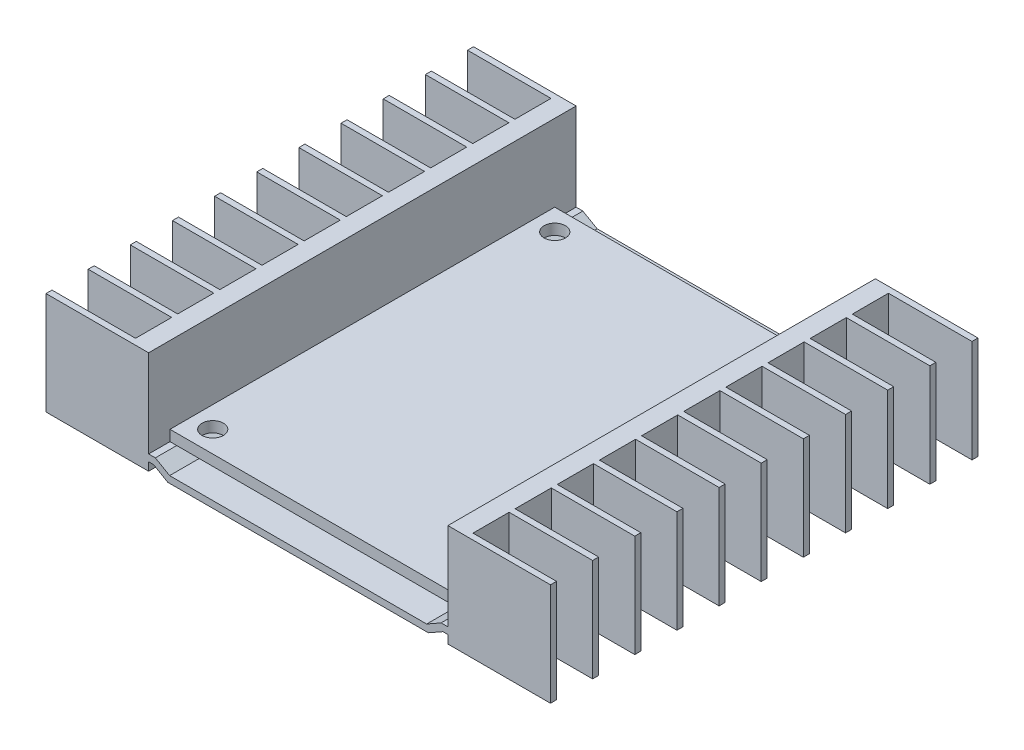
SolidWorks part; units mm, degrees
ref_plane "Front Plane" through (0, 0, 0) normal (0, 0, 1) x (1, 0, 0)
ref_plane "Top Plane" through (0, 0, 0) normal (0, 1, 0) x (1, 0, 0)
ref_plane "Right Plane" through (0, 0, 0) normal (1, 0, 0) x (0, 0, -1)
sketch "Sketch1" plane through (0, 0, 0) normal (0, 1, 0) x (1, 0, 0)
  line L1 (-99.1601, -6.7891) -> (-24.2301, -6.7891) construction
  line L2 (-99.1601, -6.7891) -> (-99.1601, -70.2891) construction
  line L3 (-99.1601, -70.2891) -> (-24.2301, -70.2891) construction
  line L4 (-24.2301, -6.7891) -> (-24.2301, -70.2891) construction
  line L5 (-83.9201, -9.9641) -> (-39.4701, -9.9641)
  line L6 (-83.9201, -9.9641) -> (-83.9201, -67.1141)
  line L7 (-83.9201, -67.1141) -> (-39.4701, -67.1141)
  line L8 (-39.4701, -9.9641) -> (-39.4701, -67.1141)
  circle A0 centre (-80.7451, -63.9391) radius 1.5875
  circle A1 centre (-42.6451, -63.9391) radius 1.5875
  circle A2 centre (-42.6451, -13.1391) radius 1.5875
  circle A3 centre (-80.7451, -13.1391) radius 1.5875
  dimension "D3" = 3.175
  dimension "D4" = 2
  dimension "D1" = 63.5
  dimension "D2" = 74.93
  dimension "D6" = 50.8
  dimension "D7" = 38.1
  dimension "D8" = 6.35
  dimension "D9" = 18.415
  dimension "D10" = 3.175
  dimension "D11" = 3.175
  dimension "D12" = 3.175
  dimension "D13" = 3.175
  dimension "D14" = 57.15
  dimension "D5" = 2
extrude "Boss-Extrude1" add sketch "Sketch1" along normal blind 1.5875
sketch "Sketch2" plane through (0, 1.5875, 0) normal (0, 1, 0) x (1, 0, 0)
  line L0 (-99.1601, -6.7891) -> (-83.9201, -6.7891)
  line L1 (-83.9201, -6.7891) -> (-83.9201, -70.2891)
  line L2 (-83.9201, -70.2891) -> (-99.1601, -70.2891)
  line L3 (-99.1601, -70.2891) -> (-99.1601, -69.3948)
  line L4 (-99.1601, -69.3948) -> (-86.7552, -69.3948)
  line L5 (-86.7552, -69.3948) -> (-86.7552, -64.0286)
  line L6 (-86.7552, -64.0286) -> (-99.1601, -64.0286)
  line L7 (-83.9201, -9.9641) -> (-83.9201, -67.1141) construction
  line L8 (-61.6951, -9.9641) -> (-61.6951, -67.1141) construction
  line L9 (-39.4701, -9.9641) -> (-83.9201, -9.9641) construction
  line L10 (-99.1601, -64.0286) -> (-99.1601, -63.1342)
  line L11 (-99.1601, -63.1342) -> (-86.7552, -63.1342)
  line L12 (-86.7552, -63.1342) -> (-86.7552, -57.768)
  line L13 (-86.7552, -57.768) -> (-99.1601, -57.768)
  line L14 (-99.1601, -57.768) -> (-99.1601, -56.8736)
  line L15 (-99.1601, -56.8736) -> (-86.7552, -56.8736)
  line L16 (-86.7552, -56.8736) -> (-86.7552, -51.5074)
  line L17 (-86.7552, -51.5074) -> (-99.1601, -51.5074)
  line L18 (-99.1601, -51.5074) -> (-99.1601, -50.6131)
  line L19 (-99.1601, -50.6131) -> (-86.7552, -50.6131)
  line L20 (-86.7552, -50.6131) -> (-86.7552, -45.2469)
  line L21 (-86.7552, -45.2469) -> (-99.1601, -45.2469)
  line L22 (-99.1601, -45.2469) -> (-99.1601, -44.3525)
  line L23 (-99.1601, -44.3525) -> (-86.7552, -44.3525)
  line L24 (-86.7552, -44.3525) -> (-86.7552, -38.9863)
  line L25 (-86.7552, -38.9863) -> (-99.1601, -38.9863)
  line L26 (-99.1601, -38.9863) -> (-99.1601, -38.0919)
  line L27 (-99.1601, -38.0919) -> (-86.7552, -38.0919)
  line L28 (-86.7552, -38.0919) -> (-86.7552, -32.7257)
  line L29 (-86.7552, -32.7257) -> (-99.1601, -32.7257)
  line L30 (-99.1601, -32.7257) -> (-99.1601, -31.8314)
  line L31 (-99.1601, -31.8314) -> (-86.7552, -31.8314)
  line L32 (-86.7552, -31.8314) -> (-86.7552, -26.4652)
  line L33 (-86.7552, -26.4652) -> (-99.1601, -26.4652)
  line L34 (-99.1601, -26.4652) -> (-99.1601, -25.5708)
  line L35 (-99.1601, -25.5708) -> (-86.7552, -25.5708)
  line L36 (-86.7552, -25.5708) -> (-86.7552, -20.2046)
  line L37 (-86.7552, -20.2046) -> (-99.1601, -20.2046)
  line L38 (-99.1601, -20.2046) -> (-99.1601, -19.3103)
  line L39 (-99.1601, -19.3103) -> (-86.7552, -19.3103)
  line L40 (-86.7552, -19.3103) -> (-86.7552, -13.9441)
  line L41 (-86.7552, -13.9441) -> (-99.1601, -13.9441)
  line L42 (-99.1601, -13.9441) -> (-99.1601, -13.0497)
  line L43 (-99.1601, -13.0497) -> (-86.7552, -13.0497)
  line L44 (-86.7552, -13.0497) -> (-86.7552, -7.6835)
  line L45 (-86.7552, -7.6835) -> (-99.1601, -7.6835)
  line L46 (-99.1601, -7.6835) -> (-99.1601, -6.7891)
  line L47 (-83.9201, -67.1141) -> (-39.4701, -67.1141) construction
  line L48 (-24.2301, -7.6835) -> (-24.2301, -6.7891)
  line L49 (-36.6349, -7.6835) -> (-24.2301, -7.6835)
  line L50 (-36.6349, -13.0497) -> (-36.6349, -7.6835)
  line L51 (-24.2301, -13.0497) -> (-36.6349, -13.0497)
  line L52 (-24.2301, -13.9441) -> (-24.2301, -13.0497)
  line L53 (-36.6349, -13.9441) -> (-24.2301, -13.9441)
  line L54 (-36.6349, -19.3103) -> (-36.6349, -13.9441)
  line L55 (-24.2301, -19.3103) -> (-36.6349, -19.3103)
  line L56 (-24.2301, -20.2046) -> (-24.2301, -19.3103)
  line L57 (-36.6349, -20.2046) -> (-24.2301, -20.2046)
  line L58 (-36.6349, -25.5708) -> (-36.6349, -20.2046)
  line L59 (-24.2301, -25.5708) -> (-36.6349, -25.5708)
  line L60 (-24.2301, -26.4652) -> (-24.2301, -25.5708)
  line L61 (-36.6349, -26.4652) -> (-24.2301, -26.4652)
  line L62 (-36.6349, -31.8314) -> (-36.6349, -26.4652)
  line L63 (-24.2301, -31.8314) -> (-36.6349, -31.8314)
  line L64 (-24.2301, -32.7257) -> (-24.2301, -31.8314)
  line L65 (-36.6349, -32.7257) -> (-24.2301, -32.7257)
  line L66 (-36.6349, -38.0919) -> (-36.6349, -32.7257)
  line L67 (-24.2301, -38.0919) -> (-36.6349, -38.0919)
  line L68 (-24.2301, -38.9863) -> (-24.2301, -38.0919)
  line L69 (-36.6349, -38.9863) -> (-24.2301, -38.9863)
  line L70 (-36.6349, -44.3525) -> (-36.6349, -38.9863)
  line L71 (-24.2301, -44.3525) -> (-36.6349, -44.3525)
  line L72 (-24.2301, -45.2469) -> (-24.2301, -44.3525)
  line L73 (-36.6349, -45.2469) -> (-24.2301, -45.2469)
  line L74 (-36.6349, -50.6131) -> (-36.6349, -45.2469)
  line L75 (-24.2301, -50.6131) -> (-36.6349, -50.6131)
  line L76 (-24.2301, -51.5074) -> (-24.2301, -50.6131)
  line L77 (-36.6349, -51.5074) -> (-24.2301, -51.5074)
  line L78 (-36.6349, -56.8736) -> (-36.6349, -51.5074)
  line L79 (-24.2301, -56.8736) -> (-36.6349, -56.8736)
  line L80 (-24.2301, -57.768) -> (-24.2301, -56.8736)
  line L81 (-36.6349, -57.768) -> (-24.2301, -57.768)
  line L82 (-36.6349, -63.1342) -> (-36.6349, -57.768)
  line L83 (-24.2301, -63.1342) -> (-36.6349, -63.1342)
  line L84 (-24.2301, -64.0286) -> (-24.2301, -63.1342)
  line L85 (-36.6349, -64.0286) -> (-24.2301, -64.0286)
  line L86 (-36.6349, -69.3948) -> (-36.6349, -64.0286)
  line L87 (-24.2301, -69.3948) -> (-36.6349, -69.3948)
  line L88 (-24.2301, -70.2891) -> (-24.2301, -69.3948)
  line L89 (-39.4701, -70.2891) -> (-24.2301, -70.2891)
  line L90 (-39.4701, -6.7891) -> (-39.4701, -70.2891)
  line L91 (-24.2301, -6.7891) -> (-39.4701, -6.7891)
  dimension "D1" = 5.3662
  dimension "D2" = 5.3662
  dimension "D8" = 5.3662
  dimension "D9" = 5.3662
  dimension "D10" = 5.3662
  dimension "D11" = 5.3662
  dimension "D12" = 5.3662
  dimension "D13" = 5.3662
  dimension "D14" = 5.3662
  dimension "D15" = 5.3662
  dimension "D16" = 0.8944
  dimension "D17" = 0.8944
  dimension "D18" = 0.8944
  dimension "D19" = 0.8944
  dimension "D20" = 0.8944
  dimension "D21" = 0.8944
  dimension "D22" = 0.8944
  dimension "D23" = 0.8944
  dimension "D24" = 0.8944
  dimension "D25" = 0.8944
  dimension "D26" = 0.8944
  dimension "D3" = 2.8351
  dimension "D27" = 2.8351
  dimension "D28" = 2.8351
  dimension "D29" = 2.8351
  dimension "D30" = 2.8351
  dimension "D31" = 2.8351
  dimension "D32" = 2.8351
  dimension "D33" = 2.8351
  dimension "D4" = 2.8351
  dimension "D5" = 2.8351
  dimension "D6" = 0
  dimension "D7" = 15.24
  dimension "D34" = 15.24
  dimension "D35" = 15.24
  dimension "D36" = 15.24
  dimension "D37" = 15.24
  dimension "D38" = 15.24
  dimension "D39" = 15.24
  dimension "D40" = 15.24
  dimension "D41" = 15.24
  dimension "D44" = 0
  dimension "D45" = 74.93
  dimension "D46" = 3.175
other "AlignGroup1"
other "AlignGroup2" parameters "D1"=2.7119, "D2"=2.2277, "D3"=11.5715, "D4"=14.2498, "D5"=70.2713, "D6"=44.45, "D7"=18.9085, "D8"=1, "D9"=3.8209, "D10"=4.0303, "D11"=4.7661, "D12"=3.0533, "D13"=3.9092, "D14"=3.6788, "D15"=1.9596, "D16"=1, "D17"=1.4702, "D18"=1.5022, "D19"=2.6471, "D20"=2.8788, "D21"=2.6947, "D22"=2.9043, "D23"=2.7554, "D24"=3.4161, "D25"=16.0578, "D26"=0.7733, "D27"=5.3662, "D28"=5.3662, "D29"=5.3662, "D30"=5.3662, "D31"=5.3662, "D32"=5.3662, "D33"=5.3662, "D34"=5.3662, "D35"=15.24, "D36"=11.5715, "D37"=11.5715, "D38"=11.5715, "D39"=11.5715, "D40"=11.5715, "D41"=11.5715, "D42"=15.24, "D43"=15.24, "D44"=63.5, "D45"=74.93, "D46"=44.45
extrude "Boss-Extrude2" add sketch "Sketch2" along normal blind 11.43 and the other way blind 3.81
sketch "Sketch4" plane through (0, 0, 70.2891) normal (0, 0, 1) x (1, 0, 0)
  line L0 (-83.9201, 0) -> (-82.9201, 0)
  line L1 (-83.9201, -2.2225) -> (-83.9201, 13.0175) construction
  line L2 (-82.9201, 0) -> (-80.8026, -1.2225)
  line L3 (-80.8026, -1.2225) -> (-42.6239, -1.2225)
  line L4 (-42.6239, -1.2225) -> (-40.4701, 0)
  line L5 (-40.4701, 0) -> (-39.4701, 0)
  line L6 (-39.4701, -2.2225) -> (-39.4701, 13.0175) construction
  line L7 (-39.4701, 0) -> (-39.4701, -1)
  line L8 (-39.4701, -1) -> (-40.206, -1)
  line L9 (-40.206, -1) -> (-42.3599, -2.2225)
  line L10 (-42.3599, -2.2225) -> (-81.0706, -2.2225)
  line L11 (-81.0706, -2.2225) -> (-83.188, -1)
  line L12 (-83.188, -1) -> (-83.9201, -1)
  line L13 (-83.9201, -1) -> (-83.9201, 0)
  line L14 (-99.1601, -2.2225) -> (-83.9201, -2.2225) construction
  line L15 (-83.9201, 0) -> (-39.4701, 0) construction
  point P18 (0, 0)
  dimension "D1" = 1
  dimension "D2" = 1
  dimension "D3" = 1
  dimension "D4" = 1
  dimension "D5" = 1
  dimension "D6" = 1
  dimension "D7" = 30
  dimension "D8" = 1
  dimension "D9" = 0
  dimension "D10" = 29.579
  dimension "D11" = 0
  dimension "D12" = 0
extrude "Boss-Extrude3" add sketch "Sketch4" against normal up to surface (63.5 mm away) up to face at (-91.5401, 5.3975, 6.7891)
equation "\"D9@Sketch1\"=(2.95-1.5)/2"
equation "\"D2@Sketch2\" = \"D1@Sketch2\""
equation "\"D8@Sketch2\"=\"D1@Sketch2\""
equation "\"D9@Sketch2\"=\"D1@Sketch2\""
equation "\"D10@Sketch2\"=\"D1@Sketch2\""
equation "\"D11@Sketch2\"=\"D1@Sketch2\""
equation "\"D12@Sketch2\"=\"D1@Sketch2\""
equation "\"D13@Sketch2\"=\"D1@Sketch2\""
equation "\"D14@Sketch2\"=\"D1@Sketch2\""
equation "\"D15@Sketch2\"=\"D1@Sketch2\""
equation "\"D17@Sketch2\"=\"D16@Sketch2\""
equation "\"D18@Sketch2\"=\"D16@Sketch2\""
equation "\"D19@Sketch2\"=\"D16@Sketch2\""
equation "\"D20@Sketch2\"=\"D16@Sketch2\""
equation "\"D21@Sketch2\"=\"D16@Sketch2\""
equation "\"D22@Sketch2\"=\"D16@Sketch2\""
equation "\"D23@Sketch2\"=\"D16@Sketch2\""
equation "\"D24@Sketch2\"=\"D16@Sketch2\""
equation "\"D25@Sketch2\"=\"D16@Sketch2\""
equation "\"D26@Sketch2\"=\"D16@Sketch2\""
equation "\"D16@Sketch2\"=2.5/71"
equation "\"D1@Sketch2\"=2.5*6/71"
equation "\"D33@Sketch2\"=\"D5@Sketch2\""
equation "\"D32@Sketch2\"=\"D5@Sketch2\""
equation "\"D31@Sketch2\"=\"D5@Sketch2\""
equation "\"D30@Sketch2\"=\"D5@Sketch2\""
equation "\"D29@Sketch2\"=\"D5@Sketch2\""
equation "\"D4@Sketch2\"=\"D5@Sketch2\""
equation "\"D28@Sketch2\"=\"D5@Sketch2\""
equation "\"D27@Sketch2\"=\"D5@Sketch2\""
equation "\"D3@Sketch2\"=\"D5@Sketch2\""
